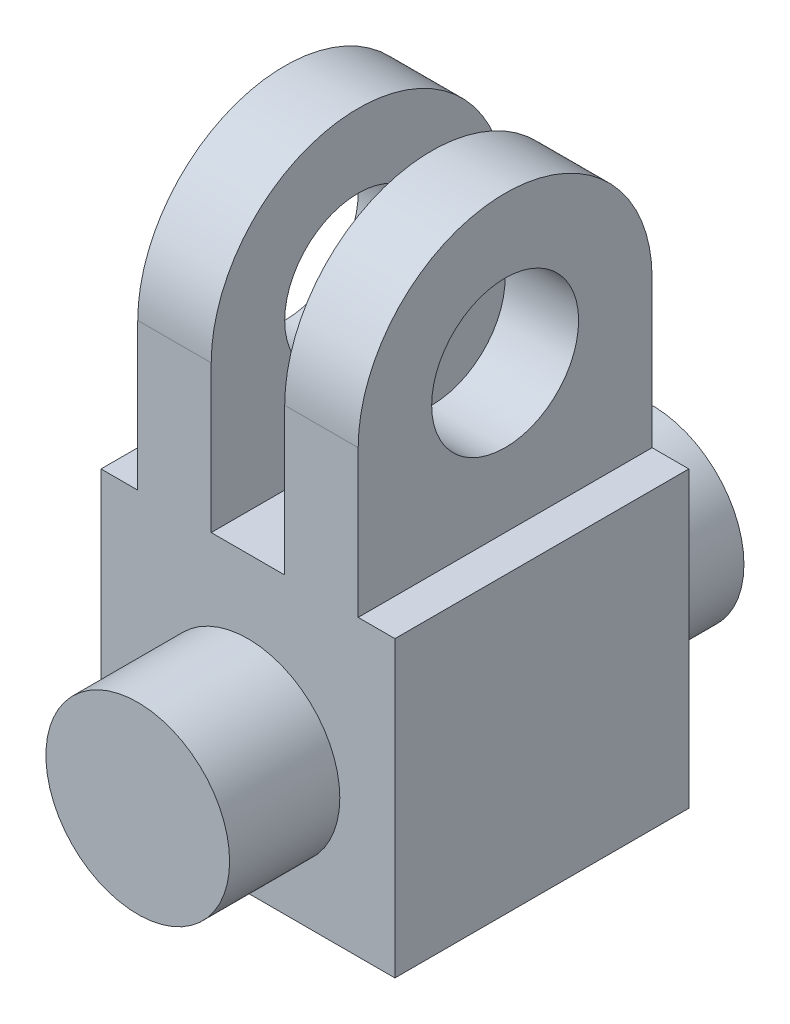
SolidWorks part; units mm, degrees
ref_plane "Alzado" through (0, 0, 0) normal (0, 0, 1) x (1, 0, 0)
ref_plane "Planta" through (0, 0, 0) normal (0, 1, 0) x (1, 0, 0)
ref_plane "Vista lateral" through (0, 0, 0) normal (1, 0, 0) x (0, 0, -1)
sketch "Croquis1" plane through (0, 0, 0) normal (0, 0, 1) x (1, 0, 0)
  line L0 (0, 40) -> (0, 108.3724) construction
  line L1 (40, -40) -> (-40, -40)
  line L2 (40, -40) -> (40, 40)
  line L3 (40, 40) -> (30, 40)
  line L4 (-40, -40) -> (-40, 40)
  line L5 (40, -40) -> (-40, 40) construction
  line L6 (40, 40) -> (-40, -40) construction
  line L7 (-30, 40) -> (-30, 80)
  line L8 (-30, 80) -> (-10, 80)
  line L9 (-10, 80) -> (-10, 40)
  line L10 (10, 80) -> (10, 40)
  line L11 (30, 40) -> (30, 80)
  line L12 (30, 80) -> (10, 80)
  line L13 (-30, 40) -> (-40, 40)
  line L14 (10, 40) -> (-10, 40)
  circle A0 centre (0, -5) radius 25
  point P0 (0, 0)
  dimension "D4" = 50
  dimension "D1" = 80
  dimension "D2" = 40
  dimension "D3" = 35
  dimension "D5" = 40
  dimension "D6" = 20
  dimension "D7" = 10
extrude "Saliente-Extruir1" add sketch "Croquis1" against normal blind 80
sketch "Croquis2" plane through (30, 0, 0) normal (1, 0, 0) x (0, 0, -1)
  line L4 (0, 80) -> (0, 40)
  line L5 (0, 40) -> (80, 40)
  line L6 (80, 40) -> (80, 80)
  line L7 (80, 80) -> (0, 80)
  line L11 (80, 80) -> (0, 80)
  arc A0 (0, 80) -> (80, 80) centre (40, 80) cw
  dimension "D2" = 40
  dimension "D1" = 0
extrude "Saliente-Extruir4" add sketch "Croquis2" against normal blind 20
sketch "Croquis4" plane through (-30, 0, 0) normal (-1, 0, 0) x (0, 0, 1)
  line L0 (-80, 80) -> (0, 80)
  arc A0 (-80, 80) -> (0, 80) centre (-40, 80) cw
  dimension "D1" = 40
extrude "Saliente-Extruir5" add sketch "Croquis4" against normal blind 20
sketch "Croquis5" plane through (-30, 0, 0) normal (-1, 0, 0) x (0, 0, 1)
  line L3 (0, 40) -> (0, 80)
  line L4 (-80, 80) -> (-80, 40)
  line L5 (-80, 40) -> (0, 40)
  line L6 (0, 40) -> (0, 80)
  line L7 (-80, 80) -> (-80, 40)
  line L8 (-80, 40) -> (0, 40)
  circle A0 centre (-40, 80) radius 20
  arc A1 (0, 80) -> (-80, 80) centre (-40, 80) ccw
  arc A2 (0, 80) -> (-80, 80) centre (-40, 80) ccw
  dimension "D2" = 40
  dimension "D1" = 0
extrude "Cortar-Extruir1" cut sketch "Croquis5" against normal through all contours A0
sketch "Croquis6" plane through (0, 0, 0) normal (0, 0, 1) x (1, 0, 0)
  circle A0 centre (0, -5) radius 25
  circle A1 centre (0, -5) radius 25 construction
  dimension "D2" = 50
extrude "Saliente-Extruir6" add sketch "Croquis6" along normal blind 30 and the other way blind 110
